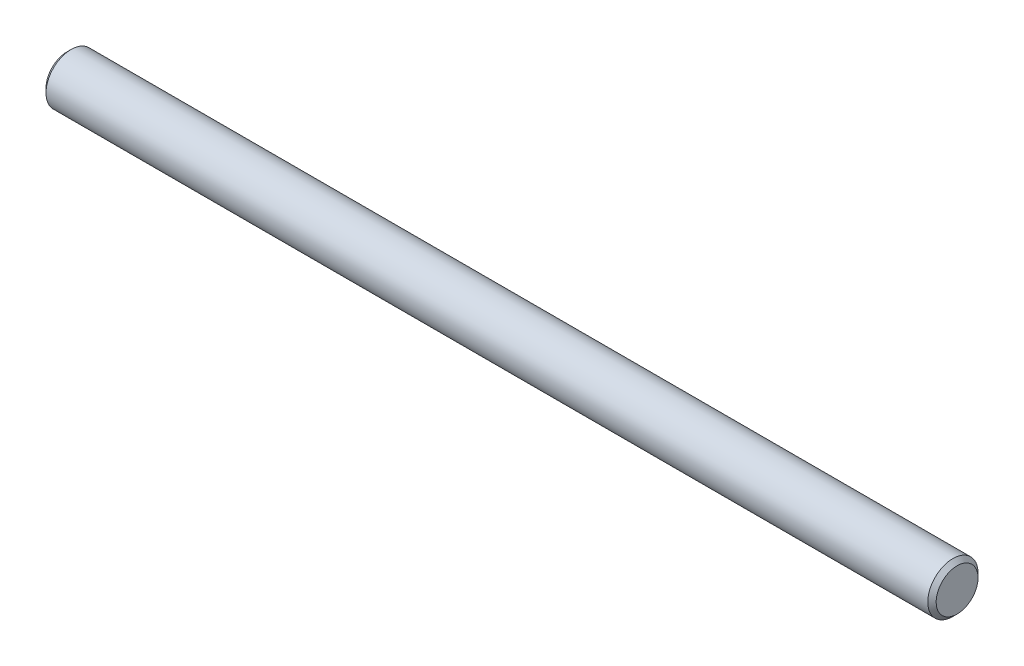
SolidWorks part; units mm, degrees
ref_plane "正面" through (0, 0, 0) normal (0, 0, 1) x (1, 0, 0)
ref_plane "平面" through (0, 0, 0) normal (0, 1, 0) x (1, 0, 0)
ref_plane "右側面" through (0, 0, 0) normal (1, 0, 0) x (0, 0, -1)
ref_plane "平面1" through (0, 0, 0) normal (0, 0, -1) x (-1, 0, 0)
sketch "ｽｹｯﾁ1" plane through (0, 0, 0) normal (0, 0, -1) x (-1, 0, 0)
  line L0 (-146.0069, 2.5174) -> (-146.0069, 0)
  line L1 (-146.0069, 0) -> (-39, 0)
  line L2 (-39, 0) -> (-39, 2.5174)
  line L3 (-39, 2.5174) -> (-39.5035, 3.0208)
  line L4 (-39.5035, 3.0208) -> (-145.5035, 3.0208)
  line L5 (-145.5035, 3.0208) -> (-146.0069, 2.5174)
  line L6 (-146.0069, 0) -> (-39, 0) construction
  dimension "D1" = 106
revolve "回転1" add sketch "ｽｹｯﾁ1" angle 360 about L6
